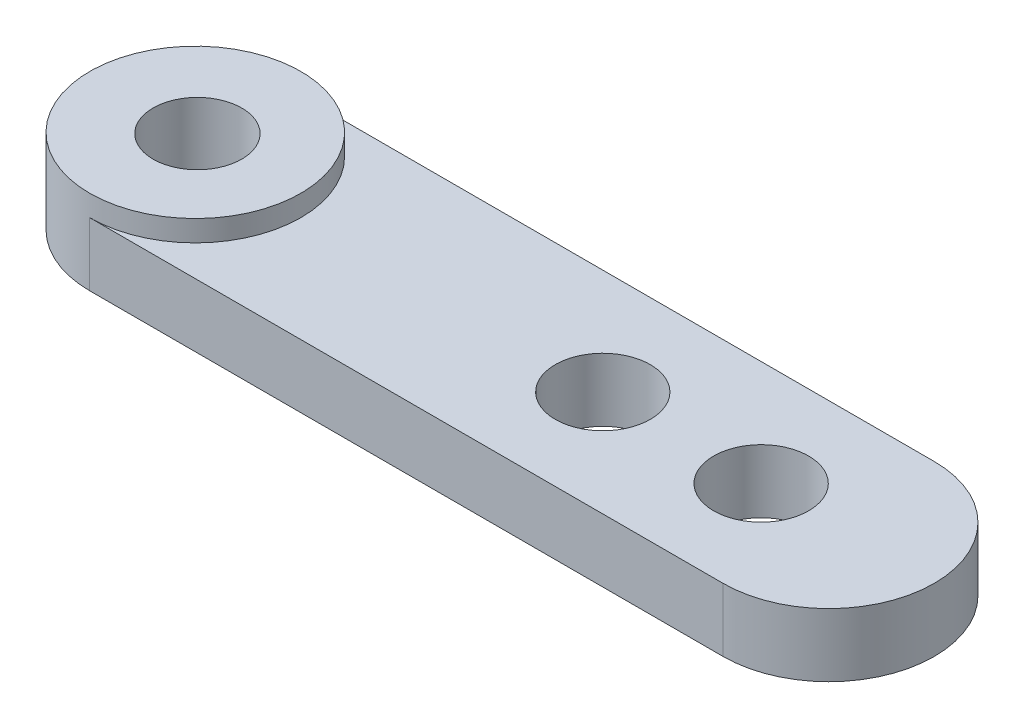
SolidWorks part; units mm, degrees
ref_plane "Front Plane" through (0, 0, 0) normal (0, 0, 1) x (1, 0, 0)
ref_plane "Top Plane" through (0, 0, 0) normal (0, 1, 0) x (1, 0, 0)
ref_plane "Right Plane" through (0, 0, 0) normal (1, 0, 0) x (0, 0, -1)
sketch "Sketch1" plane through (0, 0, 0) normal (0, 1, 0) x (1, 0, 0)
  line L0 (0, 0) -> (30, 0) construction
  line L1 (0, 5) -> (30, 5)
  line L2 (0, -5) -> (30, -5)
  arc A0 (0, 5) -> (0, -5) centre (0, 0) ccw
  arc A1 (30, -5) -> (30, 5) centre (30, 0) ccw
  circle A2 centre (0.1, 0) radius 2.1
  circle A3 centre (19.3, 0) radius 2.25
  circle A4 centre (26.8, 0) radius 2.25
  point P3 (15, 0)
  point P10 (-5, 0)
  point P15 (0, 0)
  point P16 (0, 0)
  point P17 (0, 0)
  point P18 (0, 0)
  dimension "D2" = 4.2
  dimension "D3" = 4.5
  dimension "D5" = 4.5
  dimension "D1" = 10
  dimension "D4" = 5.1
  dimension "D6" = 19.3
  dimension "D7" = 30
  dimension "D8" = 7.5
extrude "Boss-Extrude1" add sketch "Sketch1" along normal blind 3
sketch "Sketch3" plane through (0, 3, 0) normal (0, 1, 0) x (1, 0, 0)
  circle A0 centre (0, 0) radius 5
  arc A1 (0, 5) -> (0, -5) centre (0, 0) ccw construction
  circle A2 centre (0.1, 0) radius 2.1
  circle A3 centre (0.1, 0) radius 2.1 construction
extrude "Boss-Extrude3" add sketch "Sketch3" along normal blind 1
